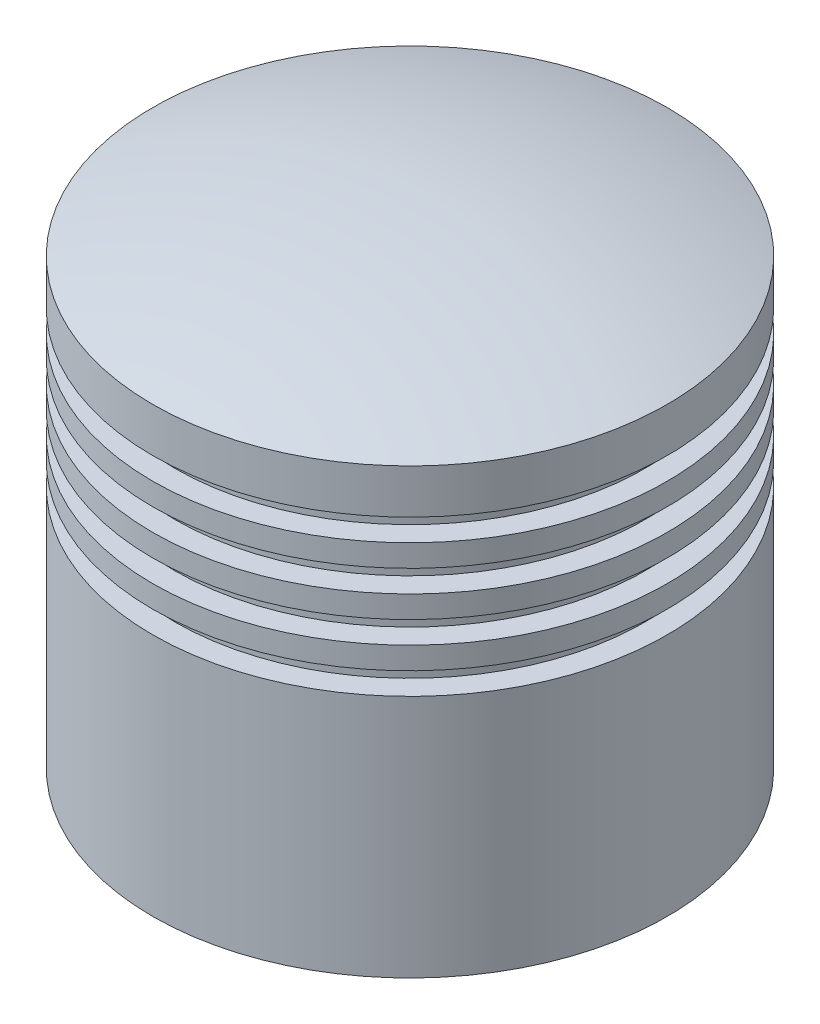
SolidWorks part; units mm, degrees
ref_plane "Front Plane" through (0, 0, 0) normal (0, 0, 1) x (1, 0, 0)
ref_plane "Top Plane" through (0, 0, 0) normal (0, 1, 0) x (1, 0, 0)
ref_plane "Right Plane" through (0, 0, 0) normal (1, 0, 0) x (0, 0, -1)
sketch "Sketch2" plane through (0, 0, 0) normal (0, 0, 1) x (1, 0, 0)
  line L0 (0, 0) -> (0, 40721.2491) construction
  line L1 (0, 0) -> (40721.2491, 0) construction
  line L2 (43, 97.3767) -> (43, 30)
  line L3 (43, 30) -> (50, 30)
  line L4 (50, 30) -> (50, 0)
  line L5 (50, 0) -> (58, 0)
  line L6 (58, 0) -> (58, 55)
  line L7 (58, 55) -> (53, 55)
  line L8 (53, 55) -> (53, 60)
  line L9 (53, 60) -> (58, 60)
  line L10 (58, 60) -> (58, 65)
  line L11 (58, 65) -> (53, 65)
  line L12 (53, 65) -> (53, 70)
  line L13 (53, 70) -> (58, 70)
  line L14 (58, 70) -> (58, 75)
  line L15 (58, 75) -> (53, 75)
  line L16 (53, 75) -> (53, 80)
  line L17 (53, 80) -> (58, 80)
  line L18 (58, 80) -> (58, 85)
  line L19 (58, 85) -> (53, 85)
  line L20 (53, 85) -> (53, 90)
  line L21 (53, 90) -> (58, 90)
  line L22 (58, 90) -> (58, 100)
  line L23 (0, 110) -> (0, 103)
  arc A0 (58, 100) -> (0, 110) centre (0.5519, -59.9991) ccw
  arc A1 (43, 97.3767) -> (0, 103) centre (0.5519, -59.9991) ccw
  point P31 (0, 0)
  point P32 (0, 0)
  dimension "D1" = 86
  dimension "D8" = 170
  dimension "D9" = 163
  dimension "D2" = 8
  dimension "D3" = 30
  dimension "D4" = 7
  dimension "D5" = 90
  dimension "D6" = 100
  dimension "D7" = 110
  dimension "D10" = 5
revolve "Revolve1" add sketch "Sketch2" angle 360 about L0
